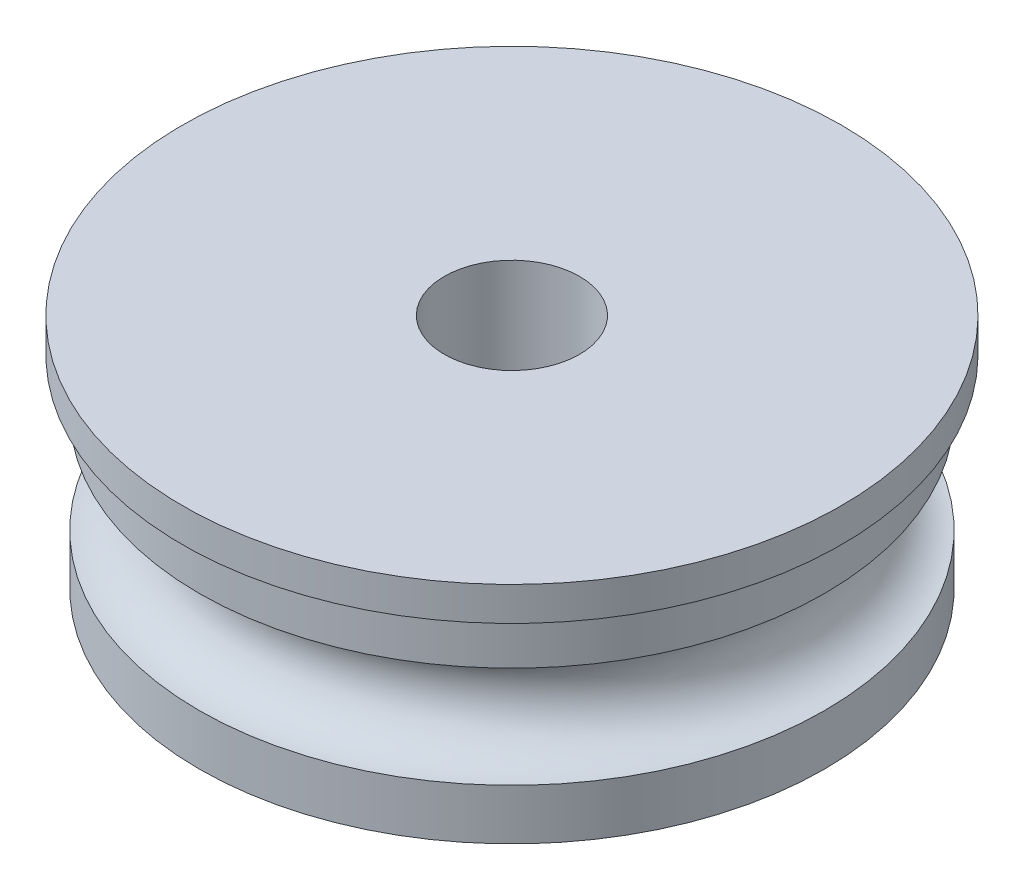
SolidWorks part; units mm, degrees
ref_plane "Front Plane" through (0, 0, 0) normal (0, 0, 1) x (1, 0, 0)
ref_plane "Top Plane" through (0, 0, 0) normal (0, 1, 0) x (1, 0, 0)
ref_plane "Right Plane" through (0, 0, 0) normal (1, 0, 0) x (0, 0, -1)
sketch "Sketch2" plane through (0, 0, 0) normal (0, 0, 1) x (1, 0, 0)
  line L0 (2, 1.6939) -> (2, 5.6939)
  line L1 (2, 5.6939) -> (9.75, 5.6939)
  line L2 (9.75, 5.6939) -> (9.75, 4.6939)
  line L3 (9.75, 4.6939) -> (9.25, 4.6939)
  line L4 (9.25, 4.6939) -> (9.25, 3.1939)
  line L5 (9.25, -1.3061) -> (6, -1.3061)
  line L6 (6, -1.3061) -> (6, 1.6939)
  line L7 (6, 1.6939) -> (2, 1.6939)
  line L8 (0, -8.6327) -> (0, 14.102) construction
  line L9 (9.25, 0.1939) -> (9.25, -1.3061)
  arc A0 (9.25, 3.1939) -> (9.25, 0.1939) centre (9.25, 1.6939) ccw
  dimension "D1" = 2
  dimension "D2" = 9.75
  dimension "D3" = 9.25
  dimension "D4" = 7
  dimension "D5" = 6
  dimension "D6" = 3
  dimension "D7" = 6
revolve "Revolve1" add sketch "Sketch2" angle 360 about L8
